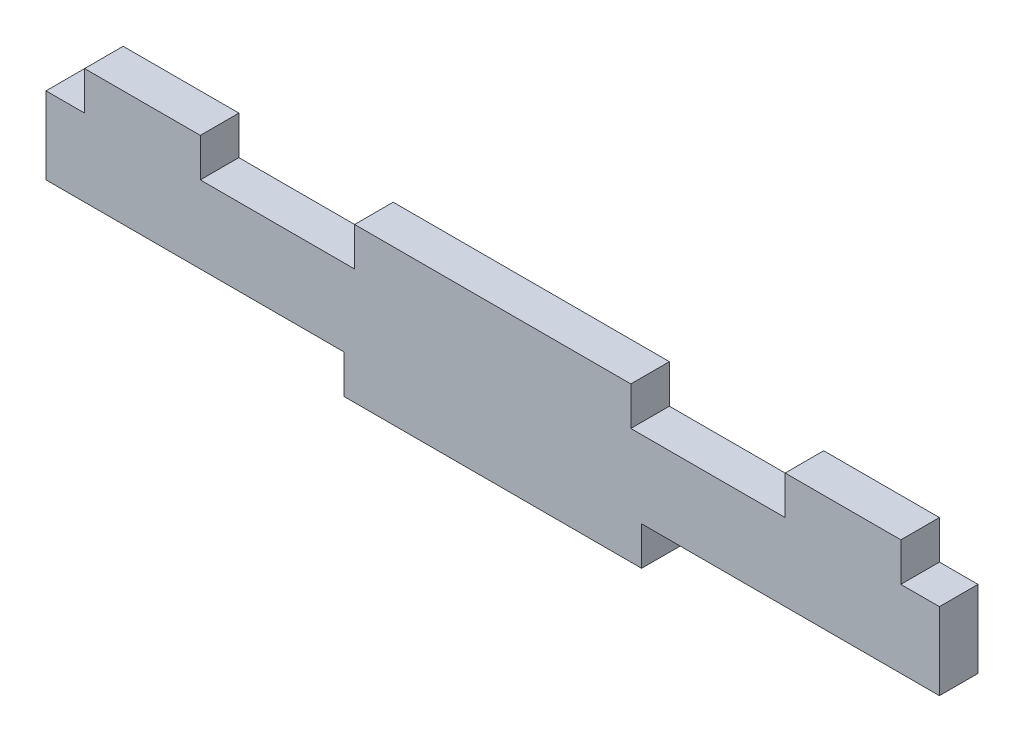
SolidWorks part; units mm, degrees
ref_plane "Alzado" through (0, 0, 0) normal (0, 0, 1) x (1, 0, 0)
ref_plane "Planta" through (0, 0, 0) normal (0, 1, 0) x (1, 0, 0)
ref_plane "Vista lateral" through (0, 0, 0) normal (1, 0, 0) x (0, 0, -1)
sketch "Croquis1" plane through (0, 0, 0) normal (0, 0, 1) x (1, 0, 0)
  line L2 (0, 0) -> (0, 5) construction
  line L3 (5, 20) -> (20, 20)
  line L6 (38.6, 0) -> (38.6, 5)
  line L8 (77.2, 0) -> (77.2, 5)
  line L9 (57.9, 15) -> (57.9, 10) construction
  line L10 (0, 15) -> (5, 15)
  line L12 (0, 5) -> (5, 5)
  line L15 (115.8, 15) -> (110.8, 15)
  line L17 (115.8, 5) -> (110.8, 5)
  line L19 (75.8, 20) -> (75.8, 15)
  line L25 (20, 20) -> (20, 15)
  line L26 (20, 15) -> (40, 15)
  line L27 (40, 20) -> (40, 15)
  line L28 (95.8, 15) -> (75.8, 15)
  line L29 (95.8, 20) -> (95.8, 15)
  line L30 (40, 20) -> (75.8, 20)
  line L31 (95.8, 20) -> (110.8, 20)
  line L32 (0, 5) -> (0, 15)
  line L33 (5, 15) -> (5, 20)
  line L35 (0, 0) -> (5, 0) construction
  line L36 (110.8, 15) -> (110.8, 20)
  line L38 (115.8, 5) -> (115.8, 15)
  line L39 (38.6, 0) -> (77.2, 0)
  line L40 (38.6, 5) -> (5, 5)
  line L41 (77.2, 5) -> (110.8, 5)
  dimension "D2" = 115.8
  dimension "D3" = 38.6
  dimension "D4" = 5
  dimension "D6" = 10
  dimension "D9" = 5
  dimension "D11" = 20
extrude "Saliente-Extruir1" add sketch "Croquis1" along normal blind 5
